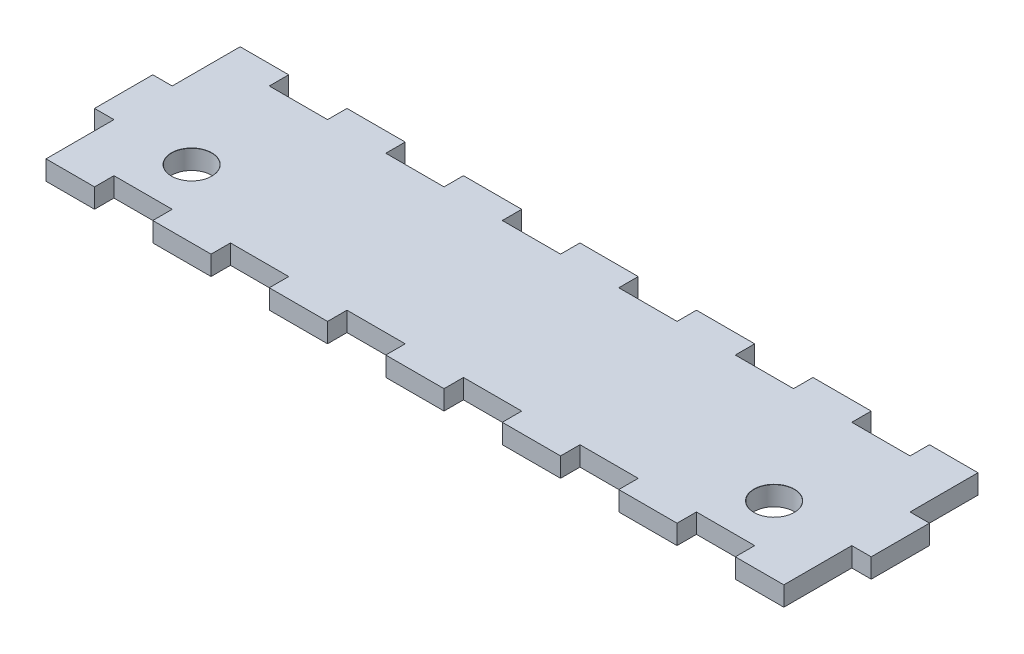
SolidWorks part; units mm, degrees
ref_plane "Front Plane" through (0, 0, 0) normal (0, 0, 1) x (1, 0, 0)
ref_plane "Top Plane" through (0, 0, 0) normal (0, 1, 0) x (1, 0, 0)
ref_plane "Right Plane" through (0, 0, 0) normal (1, 0, 0) x (0, 0, -1)
sketch "Sketch1" plane through (0, 0, 0) normal (0, 1, 0) x (1, 0, 0)
  line L0 (57, 15) -> (49.5, 15)
  line L1 (49.5, 15) -> (49.5, 12)
  line L2 (49.5, 12) -> (40.5, 12)
  line L3 (40.5, 12) -> (40.5, 15)
  line L4 (40.5, 15) -> (31.5, 15)
  line L5 (31.5, 15) -> (31.5, 12)
  line L6 (31.5, 12) -> (22.5, 12)
  line L7 (22.5, 12) -> (22.5, 15)
  line L8 (22.5, 15) -> (13.5, 15)
  line L9 (13.5, 15) -> (13.5, 12)
  line L10 (13.5, 12) -> (4.5, 12)
  line L11 (4.5, 12) -> (4.5, 15)
  line L12 (4.5, 15) -> (-4.5, 15)
  line L13 (-4.5, 15) -> (-4.5, 12)
  line L14 (-4.5, 12) -> (-13.5, 12)
  line L15 (-13.5, 12) -> (-13.5, 15)
  line L16 (-13.5, 15) -> (-22.5, 15)
  line L17 (-22.5, 15) -> (-22.5, 12)
  line L18 (-22.5, 12) -> (-31.5, 12)
  line L19 (-31.5, 12) -> (-31.5, 15)
  line L20 (-31.5, 15) -> (-40.5, 15)
  line L21 (-40.5, 15) -> (-40.5, 12)
  line L22 (-40.5, 12) -> (-49.5, 12)
  line L23 (-49.5, 12) -> (-49.5, 15)
  line L24 (-49.5, 15) -> (-57, 15)
  line L25 (-57, 15) -> (-57, 12)
  line L26 (-57, 12) -> (-57, 4.5)
  line L27 (-57, 4.5) -> (-60, 4.5)
  line L28 (-60, 4.5) -> (-60, -4.5)
  line L29 (-60, -4.5) -> (-57, -4.5)
  line L30 (-57, -4.5) -> (-57, -12)
  line L31 (-57, -12) -> (-57, -15)
  line L32 (-57, -15) -> (-49.5, -15)
  line L33 (-49.5, -15) -> (-49.5, -12)
  line L34 (-49.5, -12) -> (-40.5, -12)
  line L35 (-40.5, -12) -> (-40.5, -15)
  line L36 (-40.5, -15) -> (-31.5, -15)
  line L37 (-31.5, -15) -> (-31.5, -12)
  line L38 (-31.5, -12) -> (-22.5, -12)
  line L39 (-22.5, -12) -> (-22.5, -15)
  line L40 (-22.5, -15) -> (-13.5, -15)
  line L41 (-13.5, -15) -> (-13.5, -12)
  line L42 (-13.5, -12) -> (-4.5, -12)
  line L43 (-4.5, -12) -> (-4.5, -15)
  line L44 (-4.5, -15) -> (4.5, -15)
  line L45 (4.5, -15) -> (4.5, -12)
  line L46 (4.5, -12) -> (13.5, -12)
  line L47 (13.5, -12) -> (13.5, -15)
  line L48 (13.5, -15) -> (22.5, -15)
  line L49 (22.5, -15) -> (22.5, -12)
  line L50 (22.5, -12) -> (31.5, -12)
  line L51 (31.5, -12) -> (31.5, -15)
  line L52 (31.5, -15) -> (40.5, -15)
  line L53 (40.5, -15) -> (40.5, -12)
  line L54 (40.5, -12) -> (49.5, -12)
  line L55 (49.5, -12) -> (49.5, -15)
  line L56 (49.5, -15) -> (57, -15)
  line L57 (57, -15) -> (57, -12)
  line L58 (57, -12) -> (57, -4.5)
  line L59 (57, -4.5) -> (60, -4.5)
  line L60 (60, -4.5) -> (60, 4.5)
  line L61 (60, 4.5) -> (57, 4.5)
  line L62 (57, 4.5) -> (57, 12)
  line L63 (57, 12) -> (57, 15)
  line L64 (-60, 4.5) -> (-60, 15) construction
  line L65 (-60, 15) -> (-57, 15) construction
  line L66 (60, -4.5) -> (60, -15) construction
  line L67 (60, -15) -> (57, -15) construction
  line L68 (-60, 15) -> (60, -15) construction
  point P64 (0, 0)
extrude "Boss-Extrude1" add sketch "Sketch1" along normal mid plane 3
sketch "Sketch2" plane through (0, 1.5, 0) normal (0, 1, 0) x (1, 0, 0)
  text T0 "Front/Back"
extrude "Cut-Extrude1" [suppressed] cut sketch "Sketch2" against normal blind 1
sketch "Sketch3" plane through (0, 1.5, 0) normal (0, 1, 0) x (1, 0, 0)
  line L0 (-45, -4.5) -> (45, -4.5) construction
  line L1 (-31.5, 15) -> (-40.5, 15) construction
  line L2 (-60, 4.5) -> (-60, -4.5) construction
  line L3 (60, -4.5) -> (60, 4.5) construction
  point P0 (-45, -4.5)
  point P1 (45, -4.5)
  dimension "D1" = 19.5
  dimension "D2" = 15
  dimension "D3" = 15
hole_wizard "Ø6.2 (6.2) Diameter Hole1" positions "Sketch3" profile "Sketch4" hole size "Ø6.2" standard "ISO" end condition through all
sketch "Sketch4" plane through (-45, 1.5, 4.5) normal (1, 0, 0) x (0, 0, 1)
  line L0 (0, 0) -> (0, 3)
  line L1 (0, 3) -> (3.1, 3)
  line L2 (3.1, 3) -> (3.1, 0.025)
  line L3 (3.1, 0.025) -> (3.125, 0)
  line L5 (3.125, 0) -> (0, 0)
  line L6 (-3.1, 0.025) -> (-3.125, 0) construction
  line L11 (0, -6.35) -> (0, 107.95) construction
  dimension "Thru Hole Dia." = 6.2
  dimension "Thru Hole Depth" = 3
  dimension "Near C'Sink Dia." = 6.25
  dimension "Near C'Sink Angle" = 90
